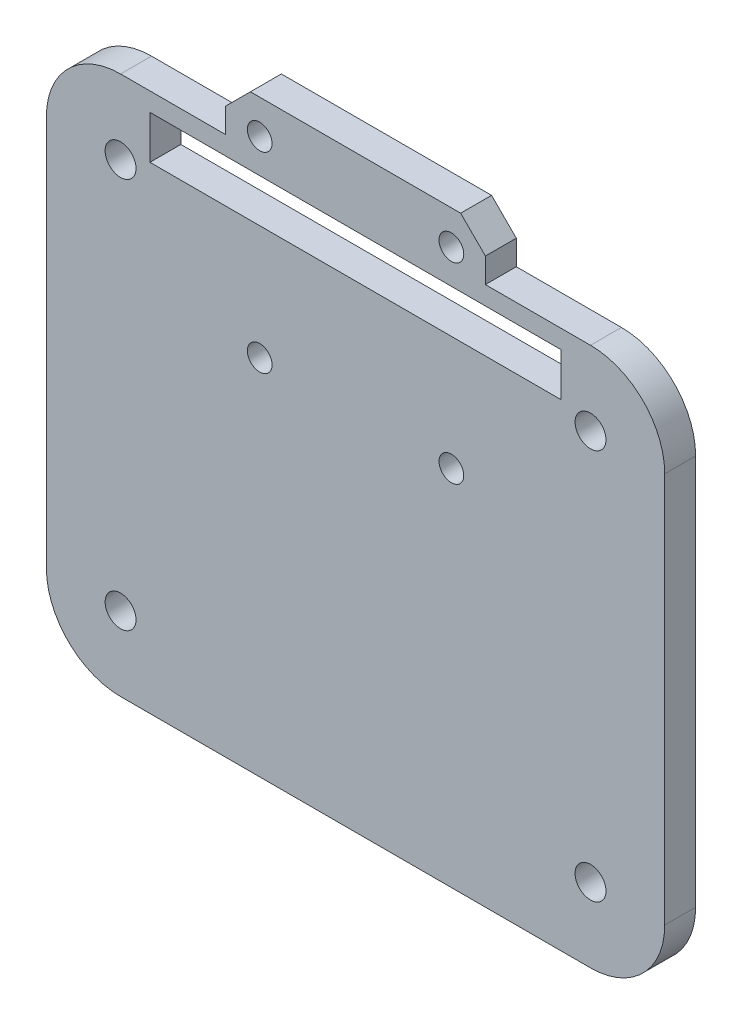
SolidWorks part; units mm, degrees
ref_plane "Ön Düzlem" through (0, 0, 0) normal (0, 0, 1) x (1, 0, 0)
ref_plane "Üst Düzlem" through (0, 0, 0) normal (0, 1, 0) x (1, 0, 0)
ref_plane "Sağ Düzlem" through (0, 0, 0) normal (1, 0, 0) x (0, 0, -1)
sketch "Çizim1" plane through (0, 0, 0) normal (0, 0, 1) x (1, 0, 0)
  line L0 (21, 43.6) -> (50, 43.6)
  line L1 (-50, -43.6) -> (50, -43.6)
  line L2 (-50, -43.6) -> (-50, 43.6)
  line L3 (-50, 43.6) -> (-21, 43.6)
  line L4 (50, -43.6) -> (50, 43.6)
  line L5 (0, 47) -> (0, -43.6) construction
  line L6 (-50, 0) -> (50, 0) construction
  line L7 (-21, 43.6) -> (-21, 47.6)
  line L8 (21, 43.6) -> (21, 47.6)
  line L9 (-17, 51.6) -> (17, 51.6)
  line L10 (21, 47.6) -> (17, 51.6)
  line L11 (-21, 47.6) -> (-17, 51.6)
  point P0 (0, 0)
  dimension "D3" = 21
  dimension "D1" = 87.2
  dimension "D2" = 100
  dimension "D4" = 21
  dimension "D5" = 8
  dimension "D6" = 4
  dimension "D7" = 4
  dimension "D8" = 4
  dimension "D9" = 4
extrude "Yükseklik-Ekstrüzyon1" add sketch "Çizim1" along normal blind 5
sketch "Çizim2" plane through (0, 0, 5) normal (0, 0, 1) x (1, 0, 0)
  line L0 (50, -43.6) -> (50, 43.6) construction
  line L2 (50, 43.6) -> (21, 43.6) construction
  line L3 (-21, 43.6) -> (-50, 43.6) construction
  line L4 (-50, 43.6) -> (-50, -43.6) construction
  circle A0 centre (38, -31.6) radius 2.5
  circle A1 centre (38, 31.6) radius 2.5
  circle A3 centre (-15.5, 46.1) radius 2
  circle A4 centre (15.5, 46.1) radius 2
  circle A5 centre (15.5, 15.1) radius 2
  circle A6 centre (-15.5, 15.1) radius 2
  circle A7 centre (-38, 31.6) radius 2.5
  circle A8 centre (-38, -31.6) radius 2.5
  dimension "D1" = 5
  dimension "D2" = 12
  dimension "D3" = 63.2
  dimension "D4" = 5
  dimension "D6" = 12
  dimension "D15" = 4
  dimension "D16" = 4
  dimension "D17" = 4
  dimension "D18" = 4
  dimension "D19" = 5
  dimension "D20" = 5
  dimension "D5" = 12
  dimension "D21" = 12
  dimension "D22" = 12
  dimension "D23" = 63.2
  dimension "D24" = 12
extrude "Kes-Ekstrüzyon1" cut sketch "Çizim2" against normal blind 10
sketch "Çizim4" plane through (0, 0, 5) normal (0, 0, 1) x (1, 0, 0)
  line L1 (-33.25, 40.6) -> (33.25, 40.6)
  line L2 (-33.25, 40.6) -> (-33.25, 33.6)
  line L3 (-33.25, 33.6) -> (33.25, 33.6)
  line L4 (33.25, 40.6) -> (33.25, 33.6)
  point P7 (0, 40.6)
  dimension "D1" = 66.5
  dimension "D2" = 7
  dimension "D3" = 40.6
extrude "Kes-Ekstrüzyon3" cut sketch "Çizim4" against normal blind 5
fillet "Radyus1" radius 12 4 edges at (-50, -43.6, 2.5) (50, -43.6, 2.5) (50, 43.6, 2.5) (-50, 43.6, 2.5)
